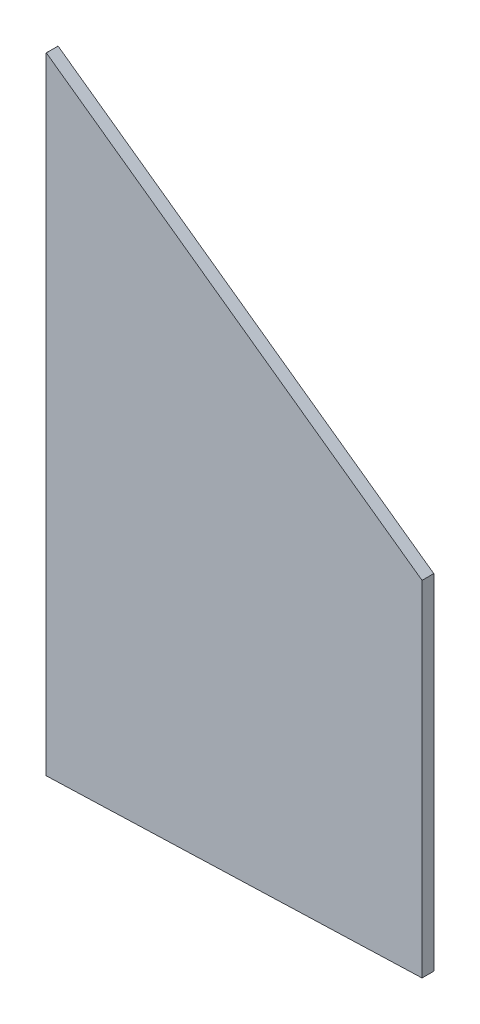
SolidWorks part; units mm, degrees
ref_plane "Front Plane" through (0, 0, 0) normal (0, 0, 1) x (1, 0, 0)
ref_plane "Top Plane" through (0, 0, 0) normal (0, 1, 0) x (1, 0, 0)
ref_plane "Right Plane" through (0, 0, 0) normal (1, 0, 0) x (0, 0, -1)
sketch "Sketch1" plane through (0, 0, 0) normal (0, 0, 1) x (1, 0, 0)
  line L0 (0, -127) -> (0, 127)
  line L1 (0, 127) -> (152.4, 17.8923)
  line L2 (152.4, 17.8923) -> (152.4, -121.8077)
  line L3 (0, -127) -> (152.4, -121.8077)
  point P4 (0, 0)
  dimension "D1" = 139.7
  dimension "D2" = 254
  dimension "D3" = 54.4
  dimension "D4" = 152.4
extrude "Boss-Extrude1" add sketch "Sketch1" along normal mid plane 4.7625
ref_plane "Plane1" through (0, 100, 0) normal (0, 1, 0) x (1, 0, 0)
sketch "Sketch4" plane through (0, 100, 0) normal (0, 1, 0) x (1, 0, 0)
  line L1 (0, 2.3813) -> (-0.0556, 2.3813)
  line L2 (0, -2.3813) -> (-0.0556, -2.3813)
  line L3 (0, -2.3813) -> (0, 2.3813)
  arc A0 (-0.0556, -2.3813) -> (-0.0556, 2.3813) centre (-51.054, 0) ccw
  dimension "D1" = 102.108
  dimension "D2" = 0.0556
  dimension "D3" = 0.0556
extrude "Boss-Extrude2" add sketch "Sketch4" along normal through all and the other way through all contours A0 L2 L3 | A0 L3 L1
